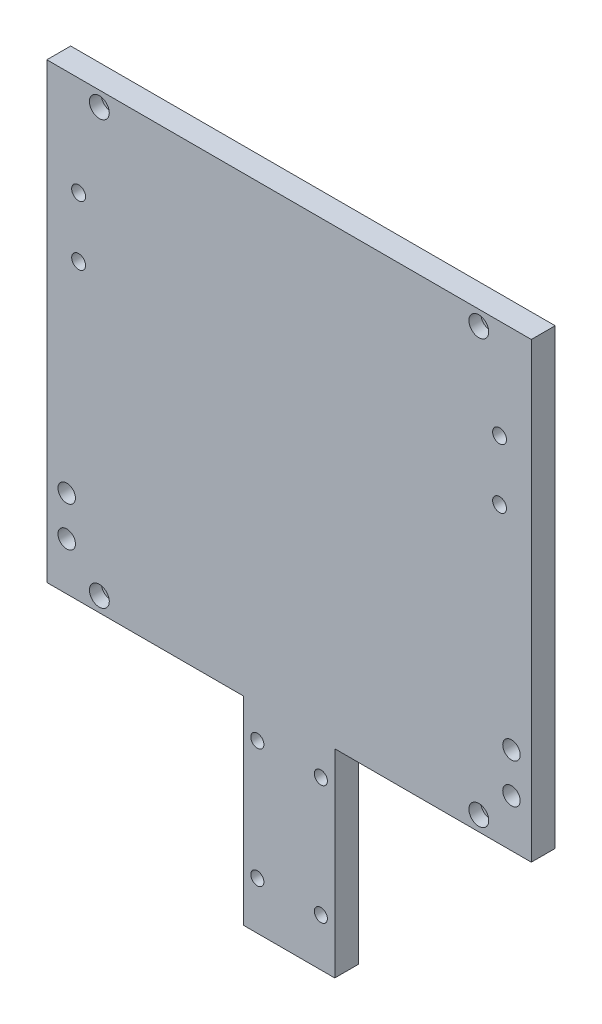
SolidWorks part; units mm, degrees
ref_plane "Front Plane" through (0, 0, 0) normal (0, 0, 1) x (1, 0, 0)
ref_plane "Top Plane" through (0, 0, 0) normal (0, 1, 0) x (1, 0, 0)
ref_plane "Right Plane" through (0, 0, 0) normal (1, 0, 0) x (0, 0, -1)
sketch "Sketch1" plane through (0, 0, 0) normal (0, 0, 1) x (1, 0, 0)
  line L1 (-61, 57) -> (61, 57)
  line L2 (-61, 57) -> (-61, -57)
  line L3 (-61, -57) -> (61, -57)
  line L4 (61, 57) -> (61, -57)
  line L5 (-61, 57) -> (61, -57) construction
  line L6 (-61, -57) -> (61, 57) construction
  point P1 (0, 0)
  dimension "D1" = 114
  dimension "D2" = 122
extrude "Boss-Extrude1" add sketch "Sketch1" along normal blind 6
sketch "Sketch2" plane through (0, 0, 6) normal (0, 0, 1) x (1, 0, 0)
  line L0 (0, -3.3) -> (0, 3.3) construction
  line L1 (3.3, 0) -> (-3.3, 0) construction
  circle A0 centre (-47.78, 53.28) radius 1.65
  circle A1 centre (47.78, 53.28) radius 1.65
  circle A2 centre (47.78, -53.28) radius 1.65
  circle A3 centre (-47.78, -53.28) radius 1.65
  dimension "D3" = 3.3
  dimension "D1" = 47.78
  dimension "D2" = 53.28
extrude "Cut-Extrude1" cut sketch "Sketch2" against normal blind 6
sketch "Sketch3" plane through (0, 0, 6) normal (0, 0, 1) x (1, 0, 0)
  line L0 (0, -3.3) -> (0, 3.3) construction
  line L1 (3.3, 0) -> (-3.3, 0) construction
  circle A0 centre (-47.78, 53.28) radius 2.5
  circle A1 centre (47.78, 53.28) radius 2.5
  circle A2 centre (47.78, -53.28) radius 2.5
  circle A3 centre (-47.78, -53.28) radius 2.5
  dimension "D1" = 5
extrude "Cut-Extrude2" cut sketch "Sketch3" against normal blind 3
sketch "Sketch4" plane through (0, 0, 6) normal (0, 0, 1) x (1, 0, 0)
  line L0 (-61, 57) -> (-61, -57) construction
  line L2 (61, 57) -> (-61, 57) construction
  line L3 (-56, -35) -> (-20.6895, -35) construction
  circle A0 centre (-53, 32) radius 1.75
  circle A1 centre (-53, 17) radius 1.75
  circle A2 centre (-56, -35) radius 2.2
  circle A3 centre (-56, -45) radius 2.2
  dimension "D3" = 3.5
  dimension "D4" = 3.5
  dimension "D9" = 4.4
  dimension "D10" = 4.4
  dimension "D1" = 8
  dimension "D2" = 25
  dimension "D5" = 15
  dimension "D7" = 5
  dimension "D6" = 52
  dimension "D8" = 10
extrude "Cut-Extrude3" cut sketch "Sketch4" against normal through all
mirror "Mirror1" about plane through (0, 0, 0) normal (1, 0, 0) of "Cut-Extrude3"
sketch "Sketch5" plane through (0, 0, 6) normal (0, 0, 1) x (1, 0, 0)
  line L0 (-61, -57) -> (61, -57) construction
  line L1 (-11.5, -57) -> (11.5, -57)
  line L2 (-11.5, -57) -> (-11.5, -107)
  line L3 (-11.5, -107) -> (11.5, -107)
  line L4 (11.5, -57) -> (11.5, -107)
  line L5 (0, -3.3) -> (0, 3.3) construction
  dimension "D1" = 23
  dimension "D2" = 11.5
  dimension "D3" = 50
extrude "Boss-Extrude2" add sketch "Sketch5" against normal through all
sketch "Sketch6" plane through (0, 0, 6) normal (0, 0, 1) x (1, 0, 0)
  line L0 (0, -3.3) -> (0, 3.3) construction
  circle A0 centre (-8, -65) radius 1.65
  circle A1 centre (-56, -45) radius 2.2 construction
  circle A2 centre (-8, -95) radius 1.65
  circle A3 centre (8, -95) radius 1.65
  circle A4 centre (8, -65) radius 1.65
  dimension "D1" = 20
  dimension "D3" = 3.3
  dimension "D5" = 3.3
  dimension "D2" = 8
  dimension "D4" = 30
extrude "Cut-Extrude4" cut sketch "Sketch6" against normal through all
equation "\"D3@Sketch4\"=3.5"
